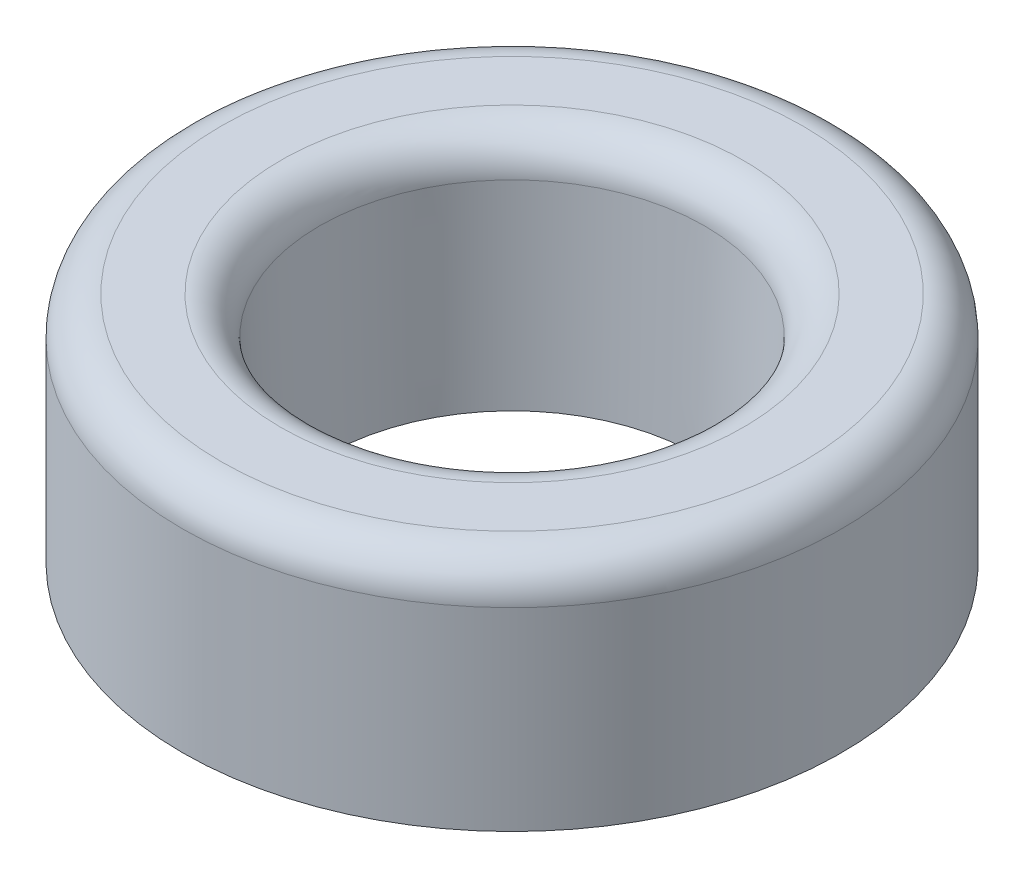
SolidWorks part; units mm, degrees
ref_plane "Front Plane" through (0, 0, 0) normal (0, 0, 1) x (1, 0, 0)
ref_plane "Top Plane" through (0, 0, 0) normal (0, 1, 0) x (1, 0, 0)
ref_plane "Right Plane" through (0, 0, 0) normal (1, 0, 0) x (0, 0, -1)
sketch "Sketch1" plane through (0, 0, 0) normal (0, 1, 0) x (1, 0, 0)
  circle A0 centre (-51.1202, 0) radius 8.5
extrude "Boss-Extrude1" add sketch "Sketch1" along normal blind 6
sketch "Sketch2" plane through (0, 6, 0) normal (0, 1, 0) x (1, 0, 0)
  circle A0 centre (-51.1202, 0) radius 5
  circle A1 centre (-51.1202, 0) radius 8.5 construction
fillet "Fillet2" radius 1 1 edges at (-51.1202, 6, 8.5)
extrude "Cut-Extrude4" cut sketch "Sketch2" against normal blind 6 draft 2 contours A0
fillet "Fillet5" radius 1 1 edges at (-51.1202, 6, 5)
equation "\".5.00mm\"=1"
